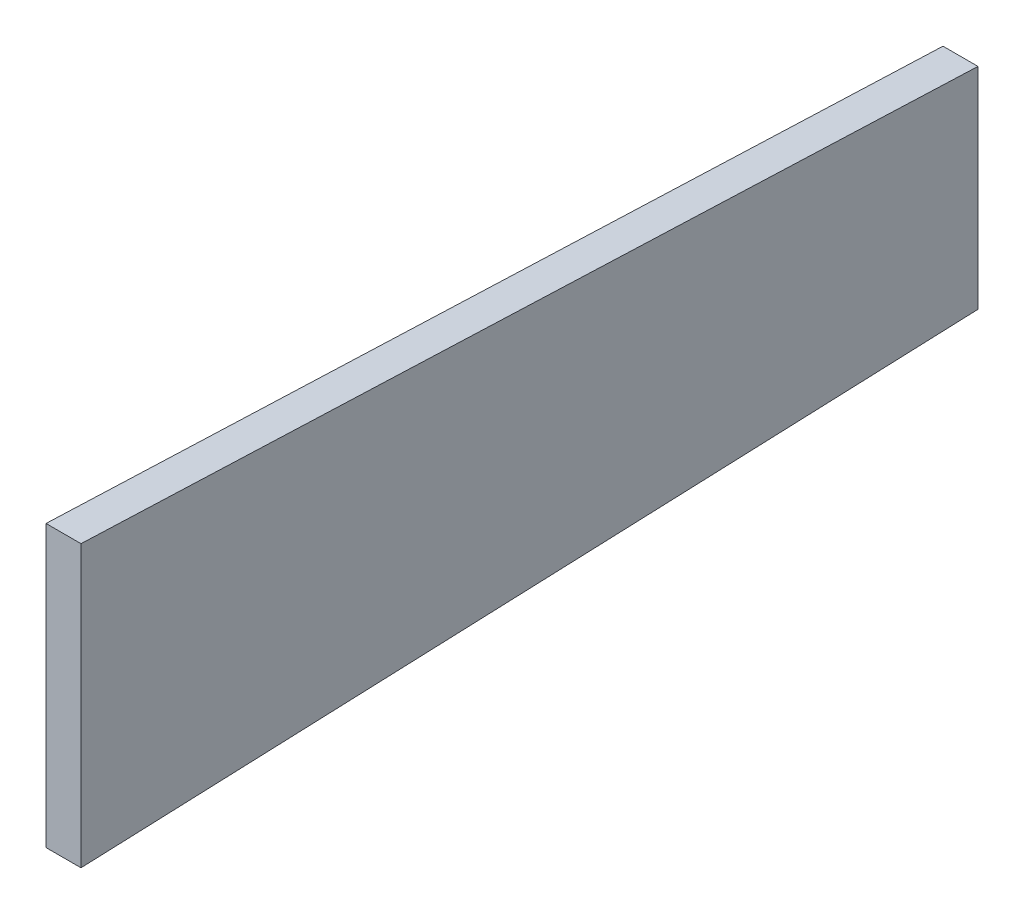
SolidWorks part; units mm, degrees
material "Perspex (TM) GS Acrylic Cast Sheet"
ref_plane "Front Plane" through (0, 0, 0) normal (0, 0, 1) x (1, 0, 0)
ref_plane "Top Plane" through (0, 0, 0) normal (0, 1, 0) x (1, 0, 0)
ref_plane "Right Plane" through (0, 0, 0) normal (1, 0, 0) x (0, 0, -1)
sketch "Sketch1" plane through (0, 0, 0) normal (1, 0, 0) x (0, 0, -1)
  line L0 (-90, 16.0391) -> (-90, -16.0391)
  line L1 (12.5, -12.0194) -> (12.5, 12.0194)
  line L19 (-90, 16.0391) -> (12.5, 12.0194)
  line L20 (-90, -16.0391) -> (12.5, -12.0194)
  circle A0 centre (0, 0) radius 4 construction
  point P2 (0, 0)
  point P18 (0, 0)
  dimension "D1" = 8
  dimension "D5" = 90
  dimension "D8" = 12.5
  dimension "D6" = 4.492
  dimension "D7" = 87.754
extrude "Boss-Extrude1" add sketch "Sketch1" along normal blind 4
sketch "Sketch2" plane through (4, 0, 0) normal (1, 0, 0) x (0, 0, -1)
  line L0 (0, 0) -> (-90, 0) construction
  line L1 (-90, 16.0391) -> (-90, -16.0391) construction
  point P0 (0, 0)
